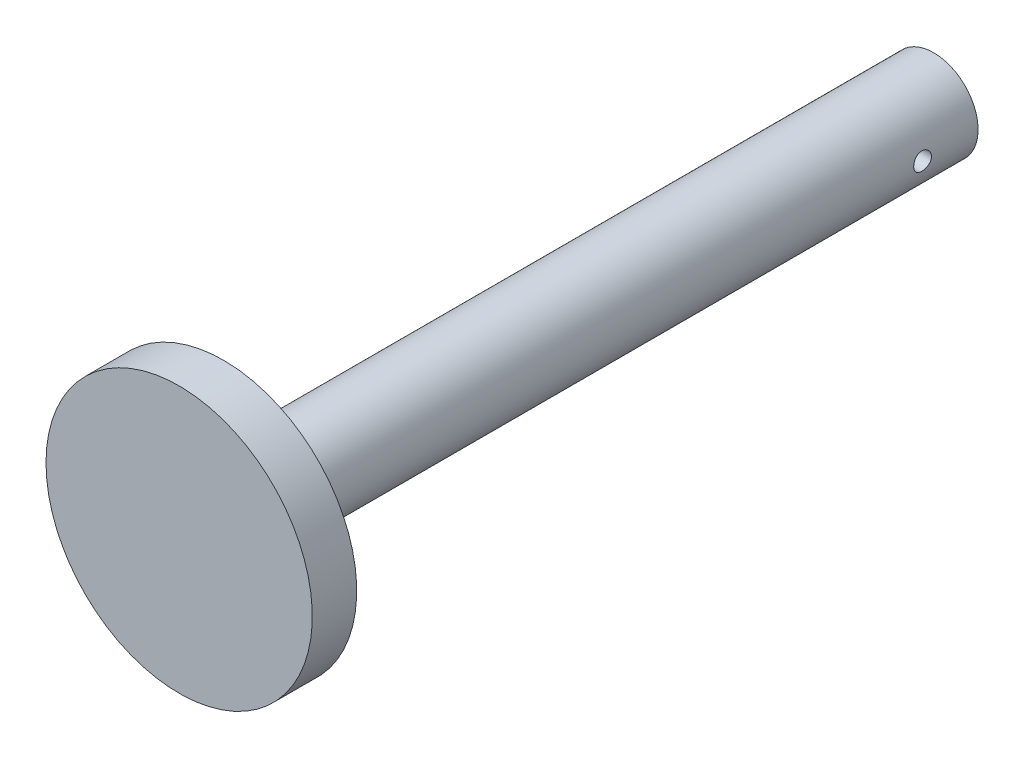
SolidWorks part; units mm, degrees
ref_plane "Front Plane" through (0, 0, 0) normal (0, 0, 1) x (1, 0, 0)
ref_plane "Top Plane" through (0, 0, 0) normal (0, 1, 0) x (1, 0, 0)
ref_plane "Right Plane" through (0, 0, 0) normal (1, 0, 0) x (0, 0, -1)
sketch "Sketch1" plane through (0, 0, 0) normal (1, 0, 0) x (0, 0, -1)
  line L0 (0, 0) -> (0, -15)
  line L1 (0, -15) -> (5, -15)
  line L2 (5, -15) -> (5, -5)
  line L3 (5, -5) -> (85, -5)
  line L4 (85, -5) -> (85, 0)
  line L5 (85, 0) -> (0, 0)
  dimension "D1" = 5
  dimension "D2" = 80
  dimension "D3" = 5
  dimension "D4" = 15
revolve "Revolve1" add sketch "Sketch1" angle 360 about L5
sketch "Sketch2" plane through (0, 0, 0) normal (1, 0, 0) x (0, 0, -1)
  line L0 (5, -5) -> (5, 5) construction
  circle A0 centre (78.75, 0) radius 1
  dimension "D1" = 2
  dimension "D2" = 73.75
extrude "Cut-Extrude1" cut sketch "Sketch2" against normal through all both and the other way through all
